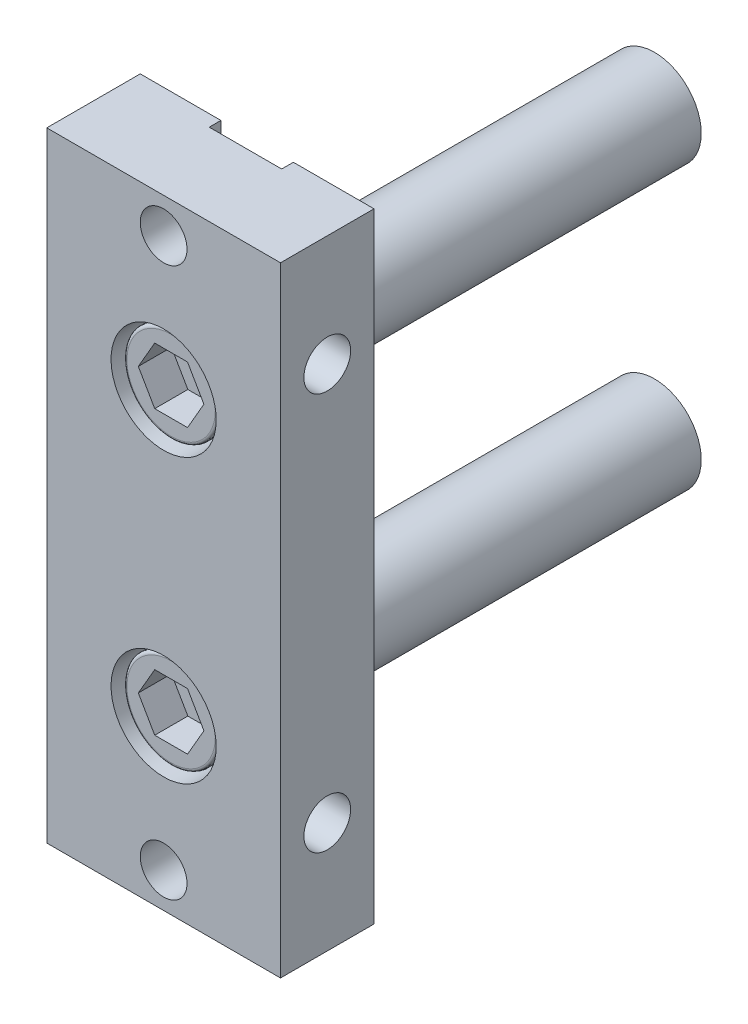
SolidWorks part; units mm, degrees
ref_plane "前视基准面" through (0, 0, 0) normal (0, 0, 1) x (1, 0, 0)
ref_plane "上视基准面" through (0, 0, 0) normal (0, 1, 0) x (1, 0, 0)
ref_plane "右视基准面" through (0, 0, 0) normal (1, 0, 0) x (0, 0, -1)
sketch "草图1" plane through (0, 0, 0) normal (1, 0, 0) x (0, 0, -1)
  line L0 (0, 0) -> (121, 0) construction
  line L1 (121, 0) -> (121, 27)
  line L2 (121, 27) -> (42, 27)
  line L3 (42, 27) -> (42, 0)
  line L4 (42, 12.1) -> (8, 12.1) construction
  line L5 (101.5, 0) -> (101.5, 6) construction
  line L6 (8, 16.1) -> (42, 16.1)
  line L7 (8, 8.1) -> (42, 8.1)
  line L8 (0, 0) -> (0, 26.5)
  line L9 (0, 26.5) -> (8, 26.5)
  line L10 (8, 26.5) -> (8, 0)
  line L11 (4, 26.5) -> (4, 0) construction
  line L12 (4, 17) -> (-1, 17) construction
  line L13 (8, 2.55) -> (9, 2.55)
  line L14 (9, 2.55) -> (9, 0)
  line L15 (0, 7.6) -> (5.5, 7.6)
  line L16 (5.5, 7.6) -> (5.5, 9.35)
  line L17 (5.5, 9.35) -> (8, 9.35)
  line L18 (71.5, 3) -> (71.5, 6.3) construction
  line L19 (81.5, 27) -> (81.5, 0) construction
  line L20 (85.5, 23.5) -> (89.9, 23.5) construction
  circle A2 centre (4, 17) radius 2
  circle A3 centre (71.5, 0) radius 3
  circle A4 centre (71.5, 0) radius 1.75
  circle A5 centre (91.5, 0) radius 3
  circle A6 centre (91.5, 0) radius 1.75
  circle A7 centre (101.5, 0) radius 2.5
  circle A8 centre (61.5, 0) radius 2.5
  circle A9 centre (81.5, 23.5) radius 4
  circle A10 centre (81.5, 23.5) radius 2.25
  point P8 (67, 0)
  point P28 (8, 15.2)
  point P44 (34, 0)
  dimension "D5" = 8
  dimension "D12" = 4
  dimension "D22" = 6
  dimension "D24" = 3.5
  dimension "D3" = 5
  dimension "D25" = 8
  dimension "D27" = 4.5
  dimension "D1" = 54
  dimension "XC" = 25
  dimension "B" = 29.5
  dimension "D4" = 54
  dimension "D6" = 6
  dimension "D7" = 24.2
  dimension "D8" = 8
  dimension "D9" = 53
  dimension "D10" = 8
  dimension "D11" = 34
  dimension "D13" = 5
  dimension "D14" = 5.1
  dimension "D15" = 1
  dimension "D16" = 6.2
  dimension "D17" = 25
  dimension "D18" = 9
  dimension "D19" = 5.5
  dimension "D20" = 5.5
  dimension "D21" = 47
  dimension "D23" = 3.3
  dimension "P" = 40
  dimension "D26" = 4.4
  dimension "E" = 39.5
  dimension "A" = 20
sketch "草图2" plane through (0, 0, 0) normal (0, 0, 1) x (1, 0, 0)
  line L0 (-10.5, 0) -> (11.5, 0) construction
  line L1 (-10.5, 27) -> (11.5, 27)
  line L2 (-10.5, 27) -> (-10.5, -27)
  line L3 (-10.5, -27) -> (11.5, -27)
  line L4 (11.5, 27) -> (11.5, -27)
  line L5 (0, 27) -> (0, -27) construction
  line L7 (-10, 26.5) -> (10, 26.5)
  line L8 (-10, 26.5) -> (-10, -26.5)
  line L9 (-10, -26.5) -> (10, -26.5)
  line L10 (10, 26.5) -> (10, -26.5)
  circle A0 centre (0, 23.5) radius 2
  point P17 (6.5, 0)
  dimension "D3" = 4
  dimension "D1" = 11.5
  dimension "D2" = 20
  dimension "D4" = 47
  dimension "D5" = 22
  dimension "D6" = 6.5
sketch "草图3" plane through (0, 0, 0) normal (0, 1, 0) x (1, 0, 0)
  line L0 (0, 0) -> (0, 121) construction
  line L1 (0, 0) -> (0, 121) construction
  line L2 (0, 9) -> (0, 34)
  line L3 (-10.5, 0) -> (11.5, 0) construction
  line L4 (-10.5, 0) -> (11.5, 0)
  line L5 (-10.5, 0) -> (-10.5, 8)
  line L6 (-10.5, 8) -> (-3.1, 8)
  line L7 (11.5, 0) -> (11.5, 8)
  line L8 (-3.1, 8) -> (-3.1, 7)
  line L9 (3.1, 8) -> (3.1, 7)
  line L10 (-3.1, 7) -> (3.1, 7)
  line L11 (3.1, 8) -> (11.5, 8)
  circle A0 centre (0, 105.5) radius 2.5
  circle A1 centre (0, 57.5) radius 2.5
  point P6 (0, 10)
  dimension "D1" = 5
  dimension "D3" = 15.5
  dimension "D2" = 15.5
  dimension "D4" = 1
  dimension "D5" = 6.2
  dimension "D6" = 3
sketch "草图4" plane through (0, 0, 0) normal (0, 0, 1) x (1, 0, 0)
  line L0 (-10.5, 23.5) -> (-10.5, 20.5) construction
  line L1 (11.5, 27) -> (11.5, -27) construction
  line L2 (-10.5, -27) -> (11.5, -27) construction
  line L3 (-10.5, 27) -> (-10.5, -27) construction
  line L4 (-5, 27) -> (-10.5, 27)
  line L5 (11.5, 27) -> (11.5, 16.85)
  line L6 (-10.5, -27) -> (5, -27)
  line L7 (-10.5, 27) -> (-10.5, 23.5)
  line L8 (0, 27) -> (0, -27) construction
  line L9 (0, 27) -> (0, -27) construction
  line L10 (5, 25.8) -> (5, 27)
  line L11 (8, 25.8) -> (8, 27)
  line L12 (-10.5, 23.5) -> (-9.3, 23.5)
  line L13 (-10.5, 20.5) -> (-9.3, 20.5)
  line L14 (-10.5, 0) -> (11.5, 0) construction
  line L15 (-10.5, 0) -> (11.5, 0) construction
  line L16 (11.5, 16.85) -> (10.5, 15.85)
  line L17 (10.5, 15.85) -> (10.5, 8.35)
  line L18 (10.5, 8.35) -> (11.5, 7.35)
  line L19 (11.5, 7.35) -> (11.5, -7.35)
  line L20 (11.5, -16.85) -> (10.5, -15.85)
  line L21 (10.5, -15.85) -> (10.5, -8.35)
  line L22 (10.5, -8.35) -> (11.5, -7.35)
  line L23 (11.5, -16.85) -> (11.5, -27)
  line L24 (-5, 27) -> (5, 27)
  line L25 (8, 27) -> (11.5, 27)
  line L26 (-10.5, 4.5) -> (-9.3, 4.5)
  line L27 (-9.3, 4.5) -> (-9.3, 5.7)
  line L28 (-9.3, 5.7) -> (-8.1, 5.7)
  line L29 (-8.1, 5.7) -> (-8.1, -5.7)
  line L30 (-9.3, -5.7) -> (-8.1, -5.7)
  line L31 (-9.3, -4.5) -> (-9.3, -5.7)
  line L32 (-10.5, -4.5) -> (-9.3, -4.5)
  line L33 (-10.5, -4.5) -> (-10.5, -20.5)
  line L34 (-10.5, 20.5) -> (-10.5, 4.5)
  line L35 (5, 27) -> (8, 27) construction
  line L36 (-10.5, -20.5) -> (-9.3, -20.5)
  line L37 (-10.5, -23.5) -> (-9.3, -23.5)
  line L38 (-10.5, -23.5) -> (-10.5, -27)
  line L39 (5, -25.8) -> (5, -27)
  line L40 (8, -25.8) -> (8, -27)
  line L41 (8, -27) -> (11.5, -27)
  arc A0 (5, 25.8) -> (8, 25.8) centre (6.5, 23.2019) ccw
  arc A1 (-9.3, 20.5) -> (-9.3, 23.5) centre (-6.7019, 22) ccw
  arc A2 (-9.3, -20.5) -> (-9.3, -23.5) centre (-6.7019, -22) cw
  arc A3 (5, -25.8) -> (8, -25.8) centre (6.5, -23.2019) cw
  point P32 (-8.1, 0)
  point P35 (10.5, 12.1)
  dimension "D1" = 3
  dimension "D2" = 3
  dimension "D3" = 1.2
  dimension "D4" = 3.5
  dimension "D5" = 1
  dimension "D7" = 9.5
  dimension "D8" = 1.2
  dimension "D9" = 9
extrude "凸台-拉伸1" add sketch "草图4" against normal up to vertex (121 mm away) from vertex at -42 starting at point (0, 27, -42)
sketch "草图5" plane through (11.5, 0, 0) normal (1, 0, 0) x (0, 0, -1)
  circle A2 centre (61.5, 0) radius 2.5
  circle A3 centre (101.5, 0) radius 2.5
  circle A4 centre (61.5, 0) radius 2.5 construction
  circle A5 centre (101.5, 0) radius 2.5 construction
extrude "P" cut sketch "草图5" against normal blind 6
cosmetic thread "装饰螺纹线1" parameters "D2"=5.1
cosmetic thread "装饰螺纹线2" parameters "D2"=5.1
sketch "草图6" plane through (-10.5, 0, 0) normal (-1, 0, 0) x (0, 0, 1)
  circle A0 centre (-71.5, 0) radius 3 construction
  circle A1 centre (-91.5, 0) radius 3 construction
  circle A2 centre (-71.5, 0) radius 3
  circle A3 centre (-91.5, 0) radius 3
extrude "切除-拉伸2" cut sketch "草图6" against normal blind 3.3
sketch "草图7" plane through (-10.5, 0, 0) normal (-1, 0, 0) x (0, 0, 1)
  circle A0 centre (-91.5, 0) radius 1.75 construction
  circle A1 centre (-71.5, 0) radius 1.75 construction
  circle A2 centre (-91.5, 0) radius 1.75
  circle A3 centre (-71.5, 0) radius 1.75
extrude "切除-拉伸3" cut sketch "草图7" against normal through all
sketch "草图24" plane through (11.5, 0, 0) normal (1, 0, 0) x (0, 0, -1)
  circle A0 centre (71.5, 0) radius 3 construction
  circle A1 centre (71.5, 0) radius 3
  circle A2 centre (91.5, 0) radius 3 construction
  circle A3 centre (91.5, 0) radius 3
extrude "切除-拉伸13" cut sketch "草图24" against normal blind 3.3
sketch "草图8" plane through (0, -27, 0) normal (0, -1, 0) x (1, 0, 0)
  circle A0 centre (0, -57.5) radius 2.5 construction
  circle A1 centre (0, -105.5) radius 2.5 construction
  circle A2 centre (0, -57.5) radius 2.5
  circle A3 centre (0, -105.5) radius 2.5
extrude "切除-拉伸4" cut sketch "草图8" against normal blind 6
cosmetic thread "装饰螺纹线3" parameters "D2"=5.1
cosmetic thread "装饰螺纹线4" parameters "D2"=5.1
sketch "草图9" plane through (0, 0, -121) normal (0, 0, -1) x (-1, 0, 0)
  line L0 (0, 0) -> (0, 27) construction
  line L2 (10.5, 0) -> (-11.5, 0) construction
  line L3 (10.5, 0) -> (-11.5, 0) construction
  circle A0 centre (0, 12.1) radius 8.05
  circle A1 centre (0, -12.1) radius 8.05
  dimension "D1" = 16.1
extrude "切除-拉伸5" cut sketch "草图9" against normal blind 1
sketch "草图10" plane through (0, 0, -42) normal (0, 0, 1) x (1, 0, 0)
  line L0 (-10.5, 0) -> (11.5, 0) construction
  line L1 (-10.5, 0) -> (11.5, 0) construction
  circle A0 centre (0, 12.1) radius 4
  circle A1 centre (0, -12.1) radius 4
extrude "切除-拉伸6" cut sketch "草图10" against normal blind 25
sketch "草图28" plane through (0, 0, -42) normal (0, 0, 1) x (1, 0, 0)
  line L1 (6.5, 5.1962) -> (2, 2.5981)
  line L2 (2, 2.5981) -> (2, -2.5981)
  line L3 (2, -2.5981) -> (6.5, -5.1962)
  line L4 (6.5, -5.1962) -> (11, -2.5981)
  line L5 (11, -2.5981) -> (11, 2.5981)
  line L6 (11, 2.5981) -> (6.5, 5.1962)
  circle A0 centre (6.5, 0) radius 4.5 construction
  dimension "D1" = 9
extrude "凸台-拉伸4" add sketch "草图28" along normal up to vertex (8 mm away) up to point (0, 0, -34)
sketch "草图29" plane through (0, 0, 0) normal (0, 1, 0) x (1, 0, 0)
  line L0 (11, 42) -> (12.7321, 42)
  line L1 (12.7321, 42) -> (12.7321, 41)
  line L2 (12.7321, 41) -> (11, 42)
  line L3 (6.5, 38) -> (6.5, 42) construction
  line L4 (6.5, 34) -> (6.5, 42) construction
  line L5 (3.5, 42) -> (9.5, 42) construction
  line L6 (11, 42) -> (6.5, 42) construction
  line L7 (6.5, 38) -> (6.5, 34) construction
  line L8 (6.5, 40) -> (11, 40) construction
  line L9 (11, 34) -> (11, 42) construction
  line L10 (6.5, 36) -> (11, 36) construction
  line L11 (6.5, 38) -> (11, 38) construction
  line L12 (12.7321, 35) -> (11, 34)
  line L13 (12.7321, 34) -> (12.7321, 35)
  line L14 (11, 34) -> (12.7321, 34)
  line L16 (12.7321, 38) -> (12.7321, 39)
  line L17 (12.7321, 39) -> (11, 38)
  line L18 (11, 38) -> (12.7321, 37)
  line L19 (12.7321, 37) -> (12.7321, 38)
  dimension "D1" = 1
  dimension "D2" = 30
revolve "切除-旋转2" cut sketch "草图29" angle 360 mid plane about L3
sketch "草图31" plane through (11.5, 0, 0) normal (1, 0, 0) x (0, 0, -1)
  circle A0 centre (81.5, 23.5) radius 2.25 construction
  circle A1 centre (81.5, 23.5) radius 2.25
extrude "切除-拉伸14" cut sketch "草图31" against normal through all
sketch "草图32" plane through (11.5, 0, 0) normal (1, 0, 0) x (0, 0, -1)
  line L0 (77.5, 23.5) -> (77.5, 27)
  line L1 (121, 27) -> (42, 27) construction
  line L3 (85.5, 23.5) -> (85.5, 27)
  line L4 (85.5, 27) -> (77.5, 27)
  circle A1 centre (81.5, 23.5) radius 4 construction
  arc A2 (77.5, 23.5) -> (85.5, 23.5) centre (81.5, 23.5) ccw
extrude "切除-拉伸15" cut sketch "草图32" against normal blind 4.4
sketch "草图33" plane through (-10.5, 0, 0) normal (-1, 0, 0) x (0, 0, 1)
  line L0 (-85.5, 23.5) -> (-85.5, 27)
  line L1 (-85.5, 27) -> (-77.5, 27)
  line L2 (-121, 27) -> (-42, 27) construction
  line L3 (-77.5, 27) -> (-77.5, 23.5)
  circle A0 centre (-81.5, 23.5) radius 4 construction
  arc A1 (-85.5, 23.5) -> (-77.5, 23.5) centre (-81.5, 23.5) ccw
extrude "切除-拉伸16" cut sketch "草图33" against normal blind 4.4
mirror "镜向6" about plane through (0, 0, 0) normal (0, 1, 0) of "切除-拉伸16", "切除-拉伸15", "切除-拉伸14"
fillet "圆角1" radius 0.9 8 edges at (-8.3, -27, -77.5) (-8.3, -27, -85.5) (9.75, -27, -77.5) (9.75, -27, -85.5) (9.75, 27, -77.5) (9.75, 27, -85.5) (-8.3, 27, -77.5) (-8.3, 27, -85.5)
sketch "草图11" plane through (0, 0, 0) normal (0, 0, 1) x (1, 0, 0)
  line L0 (-10, -26.5) -> (10, -26.5) construction
  line L1 (10, 26.5) -> (10, -26.5) construction
  line L2 (-10, 26.5) -> (-10, -26.5) construction
  line L3 (-10, 26.5) -> (10, 26.5) construction
  line L4 (-10, -26.5) -> (10, -26.5)
  line L5 (10, 26.5) -> (10, -26.5)
  line L6 (-10, 26.5) -> (-10, -26.5)
  line L7 (-10, 26.5) -> (10, 26.5)
extrude "凸台-拉伸2" add sketch "草图11" against normal up to vertex (8 mm away) separate body up to point (0, 26.5, -8)
sketch "草图12" plane through (0, 26.5, 0) normal (0, 1, 0) x (1, 0, 0)
  line L0 (-3.1, 8) -> (-3.1, 7) construction
  line L1 (-3.1, 7) -> (3.1, 7) construction
  line L2 (3.1, 8) -> (3.1, 7) construction
  line L3 (-3.1, 8) -> (-3.1, 7)
  line L4 (-3.1, 7) -> (3.1, 7)
  line L5 (3.1, 8) -> (3.1, 7)
  line L6 (-3.1, 8) -> (3.1, 8)
extrude "切除-拉伸7" cut sketch "草图12" against normal through all
sketch "草图13" plane through (0, 0, 0) normal (1, 0, 0) x (0, 0, -1)
  line L0 (0, 7.6) -> (5.5, 7.6) construction
  line L1 (5.5, 7.6) -> (5.5, 9.35) construction
  line L2 (5.5, 9.35) -> (8, 9.35) construction
  line L3 (0, 7.6) -> (5.5, 7.6)
  line L4 (5.5, 7.6) -> (5.5, 9.35)
  line L5 (5.5, 9.35) -> (8, 9.35)
  line L6 (42, 12.1) -> (8, 12.1) construction
  line L7 (42, 12.1) -> (8, 12.1) construction
  line L8 (0, 7.6) -> (0, 12.1)
  line L9 (0, 0) -> (0, 26.5) construction
  line L10 (0, 12.1) -> (8, 12.1)
  line L11 (8, 12.1) -> (8, 9.35)
revolve "切除-旋转1" cut sketch "草图13" angle 360 mid plane about L7
sketch "草图18" plane through (0, 0, 0) normal (0, 0, 1) x (1, 0, 0)
  circle A0 centre (0, 23.5) radius 2 construction
  circle A1 centre (0, 23.5) radius 2
extrude "切除-拉伸10" cut sketch "草图18" against normal through all
cosmetic thread "装饰螺纹线5" parameters "D2"=4.1
mirror "镜向1" about plane through (0, 0, 0) normal (0, 1, 0) of "切除-拉伸10", "切除-旋转1"
sketch "草图19" plane through (10, 0, 0) normal (1, 0, 0) x (0, 0, -1)
  circle A0 centre (4, 17) radius 2 construction
  circle A1 centre (4, 17) radius 2
extrude "切除-拉伸11" cut sketch "草图19" against normal blind 5
cosmetic thread "装饰螺纹线6" parameters "D2"=4.1
mirror "镜向2" about plane through (0, 0, 0) normal (0, 1, 0) of "切除-拉伸11"
mirror "镜向3" about plane through (0, 0, 0) normal (1, 0, 0) of "镜向2", "切除-拉伸11"
sketch "螺钉草图1" plane through (-2.0166, 5.7609, -5.5) normal (0, 0, 1) x (1, 0, 0)
  circle A0 centre (2.0166, 6.3391) radius 4.05
  dimension "D1" = 8.1
extrude "拉伸-螺钉(内六角)" add sketch "螺钉草图1" along normal blind 4.86
fillet "圆角-螺钉(内六角)" radius 0.27 1 edges at (4.05, 12.1, -0.64)
sketch "螺钉草图2" plane through (0, 6.5, -0.64) normal (0, 0, 1) x (1, 0, 0)
  line L1 (2.8059, 5.6) -> (1.403, 8.03)
  line L2 (1.403, 8.03) -> (-1.403, 8.03)
  line L3 (-1.403, 8.03) -> (-2.8059, 5.6)
  line L4 (-2.8059, 5.6) -> (-1.403, 3.17)
  line L5 (-1.403, 3.17) -> (1.403, 3.17)
  line L6 (1.403, 3.17) -> (2.8059, 5.6)
  circle A0 centre (0, 5.6) radius 2.43 construction
  dimension "D1" = 4.86
extrude "切除-螺钉(内六角)" cut sketch "螺钉草图2" against normal blind 2.835
other "螺钉头<1>"
mirror "镜向5" about plane through (0, 0, 0) normal (0, 1, 0) of "拉伸-螺钉(内六角)", "圆角-螺钉(内六角)", "切除-螺钉(内六角)"
sketch "草图30" plane through (0, 0, -8) normal (0, 0, -1) x (-1, 0, 0)
  line L1 (-3.1, -26.5) -> (-3.1, 26.5) construction
  circle A0 centre (-6.5, 0) radius 2.4
  point P3 (-4.1, 0)
  dimension "D1" = 1
extrude "凸台-拉伸5" add sketch "草图30" along normal up to vertex
sketch "草图20" plane through (0, 0, 0) normal (1, 0, 0) x (0, 0, -1)
  line L1 (7, 16.1) -> (42, 16.1)
  line L2 (7, 16.1) -> (7, 12.1)
  line L3 (7, 12.1) -> (42, 12.1)
  line L4 (42, 16.1) -> (42, 12.1)
revolve "旋转1" add sketch "草图20" angle 360 mid plane about L3
sketch "草图21" plane through (0, 0, 0) normal (0, 1, 0) x (1, 0, 0)
  line L1 (3.1, 10) -> (4, 10) construction
  line L2 (3.1, 10) -> (3.1, 7)
  line L3 (3.1, 7) -> (4, 7)
  line L4 (4, 10) -> (4, 7)
  line L5 (4, 7) -> (4, 42) construction
  line L6 (0, 4) -> (0, -1) construction
  line L7 (0, 4) -> (0, -1) construction
  line L8 (-4, 10) -> (-4, 7)
  line L9 (-3.1, 7) -> (-4, 7)
  line L10 (-3.1, 10) -> (-3.1, 7)
  line L11 (-3.1, 10) -> (-4, 10) construction
  line L12 (4, 11) -> (4, 10)
  line L13 (-4, 11) -> (-4, 10)
  arc A0 (3.1, 10) -> (4, 11) centre (4.1056, 10) cw
  arc A1 (-3.1, 10) -> (-4, 11) centre (-4.1056, 10) ccw
  dimension "D1" = 1
extrude "切除-拉伸12" cut sketch "草图21" against normal through all and the other way through all
mirror "镜向4" about plane through (0, 0, 0) normal (0, 1, 0)
combine bodies "组合1" operation type add bodies to combine 131 122 123
delete or keep bodies "实体-删除1" type delete bodies bodies 135
